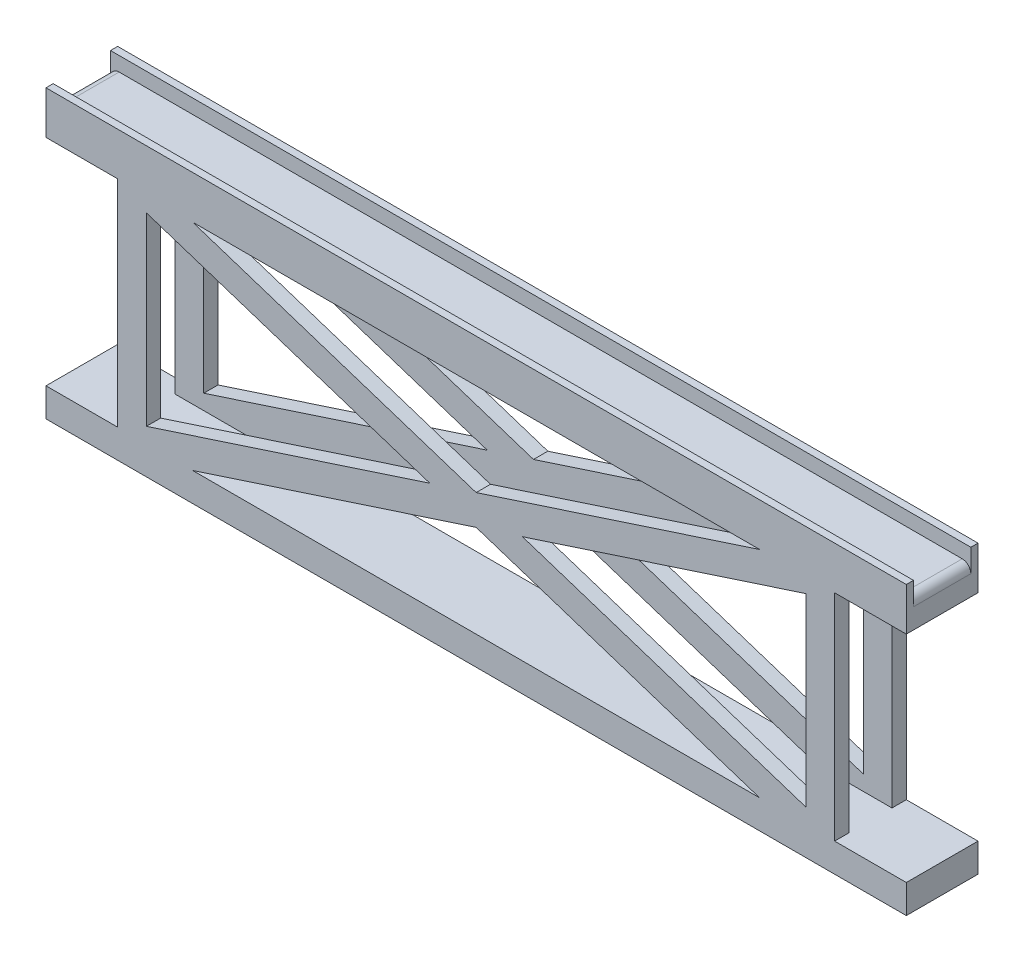
SolidWorks part; units mm, degrees
ref_plane "Plano frontal" through (0, 0, 0) normal (0, 0, 1) x (1, 0, 0)
ref_plane "Plano superior" through (0, 0, 0) normal (0, 1, 0) x (1, 0, 0)
ref_plane "Plano direito" through (0, 0, 0) normal (1, 0, 0) x (0, 0, -1)
sketch "Esboço1" plane through (0, 0, 0) normal (0, 1, 0) x (1, 0, 0)
  line L1 (0, 0) -> (3000, 0)
  line L2 (0, 0) -> (0, 250)
  line L3 (0, 250) -> (3000, 250)
  line L4 (3000, 0) -> (3000, 250)
  dimension "D1" = 3000
  dimension "D2" = 250
extrude "Ressalto-extrusão1" add sketch "Esboço1" along normal blind 1000
sketch "Esboço2" plane through (0, 0, 0) normal (0, 0, 1) x (1, 0, 0)
  line L0 (0, 1000) -> (0, 0) construction
  line L1 (0, 100) -> (250, 100)
  line L2 (0, 100) -> (0, 850)
  line L3 (0, 850) -> (250, 850)
  line L4 (250, 100) -> (250, 850)
  line L5 (3000, 1000) -> (3000, 0) construction
  line L6 (350, 850) -> (2650, 850)
  line L7 (350, 850) -> (350, 100)
  line L8 (350, 100) -> (2650, 100)
  line L9 (2650, 850) -> (2650, 100)
  line L10 (3000, 850) -> (2750, 850)
  line L11 (3000, 850) -> (3000, 100)
  line L12 (3000, 100) -> (2750, 100)
  line L13 (2750, 850) -> (2750, 100)
  line L14 (0, 0) -> (3000, 0) construction
  line L15 (0, 1000) -> (3000, 1000) construction
  line L16 (350, 797.4088) -> (2488.7204, 100)
  line L17 (511.2796, 850) -> (2650, 152.5912)
  line L18 (350, 152.5912) -> (2488.7204, 850)
  line L19 (511.2796, 100) -> (2650, 797.4088)
  line L20 (350, 100) -> (2650, 850) construction
  line L21 (350, 850) -> (2650, 100) construction
  line M18 (3000, 0) -> (3000, 1000)
  line M20 (0, 1000) -> (0, 0)
  dimension "D1" = 100
  dimension "D2" = 100
  dimension "D3" = 100
  dimension "D4" = 150
  dimension "D5" = 250
  dimension "D6" = 100
  dimension "D7" = 100
extrude "Corte-extrusão1" cut sketch "Esboço2" against normal blind 250 contours L1 L4 L3 M20 | L7 L18 L16 | L17 L18 L6 | L19 L8 L16 | L19 L17 L9 | L10 L13 L12 M18
sketch "Esboço3" plane through (250, 0, 0) normal (-1, 0, 0) x (0, 0, 1)
  line L0 (-125, 850) -> (-125, 100) construction
  line L1 (-250, 850) -> (0, 850) construction
  line L2 (-250, 100) -> (0, 100) construction
  line L4 (-200, 850) -> (-50, 850)
  line L5 (-200, 850) -> (-200, 100)
  line L6 (-200, 100) -> (-50, 100)
  line L7 (-50, 850) -> (-50, 100)
  dimension "D1" = 150
extrude "Corte-extrusão2" cut sketch "Esboço3" against normal up to surface (2500 mm away) up to face at (2750, 475, -125)
sketch "Esboço4" plane through (0, 1000, 0) normal (0, 1, 0) x (1, 0, 0)
  line L0 (3000, 125) -> (0, 125) construction
  line L1 (3000, 0) -> (3000, 250) construction
  line L2 (0, 250) -> (0, 0) construction
  line L4 (3000, 225) -> (0, 225)
  line L5 (3000, 225) -> (3000, 25)
  line L6 (3000, 25) -> (0, 25)
  line L7 (0, 225) -> (0, 25)
  dimension "D1" = 200
extrude "Corte-extrusão3" cut sketch "Esboço4" against normal blind 50
fillet "Filete1" radius 30 2 edges at (3000, 950, -125) (0, 950, -125)
